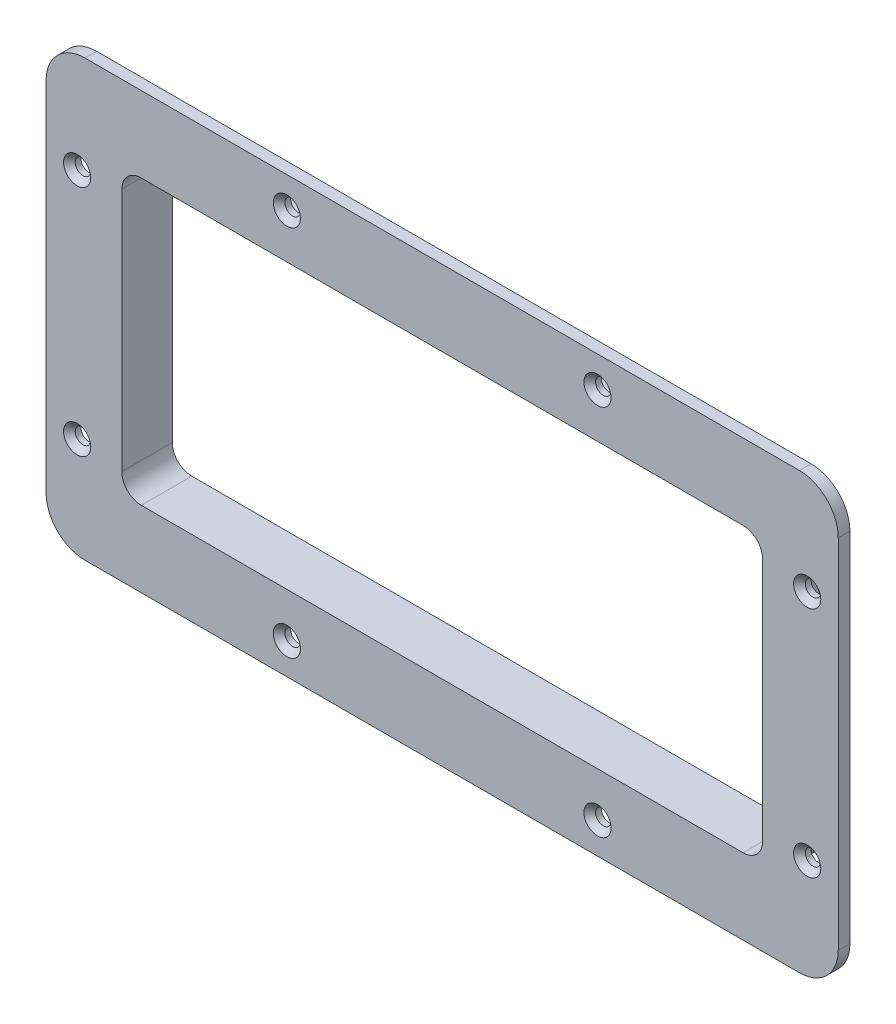
SolidWorks part; units mm, degrees
ref_plane "Front" through (0, 0, 0) normal (0, 0, 1) x (1, 0, 0)
ref_plane "Top" through (0, 0, 0) normal (0, 1, 0) x (1, 0, 0)
ref_plane "Right" through (0, 0, 0) normal (1, 0, 0) x (0, 0, -1)
sketch "Esquisse1" plane through (0, 0, 0) normal (0, 0, 1) x (1, 0, 0)
  line L0 (172, 40) -> (168.5, 40) construction
  line L1 (0, 0) -> (172, 0)
  line L2 (0, 0) -> (0, 80)
  line L3 (0, 80) -> (172, 80)
  line L4 (172, 0) -> (172, 80)
  line L5 (3.5, 76.5) -> (168.5, 76.5)
  line L6 (3.5, 76.5) -> (3.5, 3.5)
  line L7 (3.5, 3.5) -> (168.5, 3.5)
  line L8 (168.5, 76.5) -> (168.5, 3.5)
  line L9 (86, 0) -> (86, 3.5) construction
  line L10 (0, 40) -> (3.5, 40) construction
  line L11 (86, 80) -> (86, 76.5) construction
  point P17 (156.8813, 15.1187)
  dimension "D1" = 172
  dimension "D2" = 80
  dimension "D3" = 3.5
extrude "Boss.-Extru.1" add sketch "Esquisse1" along normal blind 10
sketch "Esquisse2" plane through (0, 0, 10) normal (0, 0, 1) x (1, 0, 0)
  line L0 (172, 40) -> (188, 40) construction
  line L1 (-16, 96) -> (188, 96)
  line L2 (-16, 96) -> (-16, -16)
  line L3 (-16, -16) -> (188, -16)
  line L4 (188, 96) -> (188, -16)
  line L5 (172, 0) -> (172, 80) construction
  line L6 (86, 0) -> (86, -16) construction
  line L7 (0, 0) -> (172, 0) construction
  line L8 (3.5, 3.5) -> (168.5, 3.5) construction
  line L9 (168.5, 3.5) -> (168.5, 76.5) construction
  line L10 (168.5, 76.5) -> (3.5, 76.5) construction
  line L11 (3.5, 76.5) -> (3.5, 3.5) construction
  line L12 (3.5, 3.5) -> (168.5, 3.5)
  line L13 (168.5, 3.5) -> (168.5, 76.5)
  line L14 (168.5, 76.5) -> (3.5, 76.5)
  line L15 (3.5, 76.5) -> (3.5, 3.5)
  dimension "D1" = 16
extrude "Boss.-Extru.2" add sketch "Esquisse2" along normal blind 3
fillet "Congé1" radius 10 4 edges at (188, -16, 11.5) (-16, -16, 11.5) (-16, 96, 11.5) (188, 96, 11.5)
fillet "Congé2" radius 5 8 edges at (0, 0, 5) (3.5, 3.5, 6.5) (0, 80, 5) (3.5, 76.5, 6.5) (172, 80, 5) (168.5, 76.5, 6.5) (168.5, 3.5, 6.5) (172, 0, 5)
sketch "Esquisse3" plane through (0, 0, 10) normal (0, 0, -1) x (-1, 0, 0)
  line L0 (-86, 96) -> (-86, -16) construction
  line L1 (-178, 96) -> (6, 96) construction
  line L2 (6, -16) -> (-178, -16) construction
  line L3 (16, 40) -> (-188, 40) construction
  line L4 (16, 86) -> (16, -6) construction
  line L5 (-188, -6) -> (-188, 86) construction
  circle A0 centre (-180, 40) radius 3.5
  circle A1 centre (8, 40) radius 3.5
  circle A2 centre (-86, -8) radius 3.5
  circle A3 centre (-86, 88) radius 3.5
  dimension "D1" = 7
  dimension "D2" = 8
  dimension "D3" = 8
extrude "Enlèv. mat.-Extru.1" cut sketch "Esquisse3" against normal blind 2 and the other way through all
sketch "Esquisse4" plane through (0, 0, 13) normal (0, 0, 1) x (1, 0, 0)
  line L0 (86, -16) -> (86, 96) construction
  line L1 (-6, -16) -> (178, -16) construction
  line L2 (178, 96) -> (-6, 96) construction
  line L3 (188, 40) -> (-16, 40) construction
  line L4 (188, -6) -> (188, 86) construction
  line L5 (-16, 86) -> (-16, -6) construction
  line L6 (-8, 70) -> (-8, 40) construction
  line L7 (180, 70) -> (180, 40) construction
  line L8 (46, 88) -> (86, 88) construction
  line L9 (46, -8) -> (86, -8) construction
  circle A0 centre (-8, 70) radius 2
  circle A1 centre (-8, 10) radius 2
  circle A2 centre (180, 10) radius 2
  circle A3 centre (180, 70) radius 2
  circle A4 centre (46, 88) radius 2
  circle A5 centre (126, 88) radius 2
  circle A6 centre (126, -8) radius 2
  circle A7 centre (46, -8) radius 2
  dimension "D1" = 30
  dimension "D2" = 4
  dimension "D3" = 40
extrude "Enlèv. mat.-Extru.2" cut sketch "Esquisse4" against normal through all both and the other way through all
chamfer "Chanfrein1" distance 1.5 angle 45 8 edges at (-6, 10, 13) (48, -8, 13) (128, -8, 13) (182, 10, 13) (182, 70, 13) (128, 88, 13) (48, 88, 13) (-6, 70, 13)
